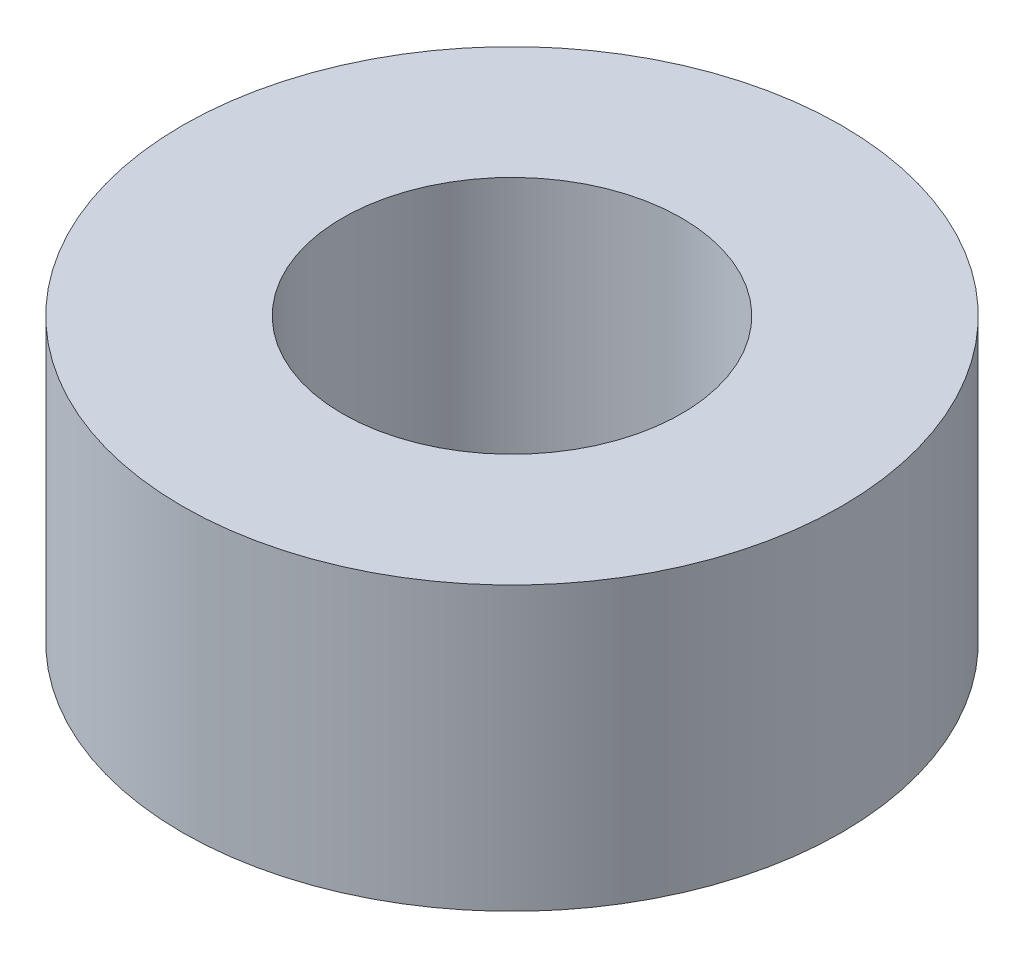
SolidWorks part; units mm, degrees
ref_plane "Front Plane" through (0, 0, 0) normal (0, 0, 1) x (1, 0, 0)
ref_plane "Top Plane" through (0, 0, 0) normal (0, 1, 0) x (1, 0, 0)
ref_plane "Right Plane" through (0, 0, 0) normal (1, 0, 0) x (0, 0, -1)
sketch "Sketch1" plane through (0, 0, 0) normal (0, 1, 0) x (1, 0, 0)
  circle A0 centre (0, 0) radius 3.5
  circle A1 centre (0, 0) radius 1.8
  dimension "D1" = 7
  dimension "D2" = 3.6
extrude "Boss-Extrude1" add sketch "Sketch1" along normal blind 3
